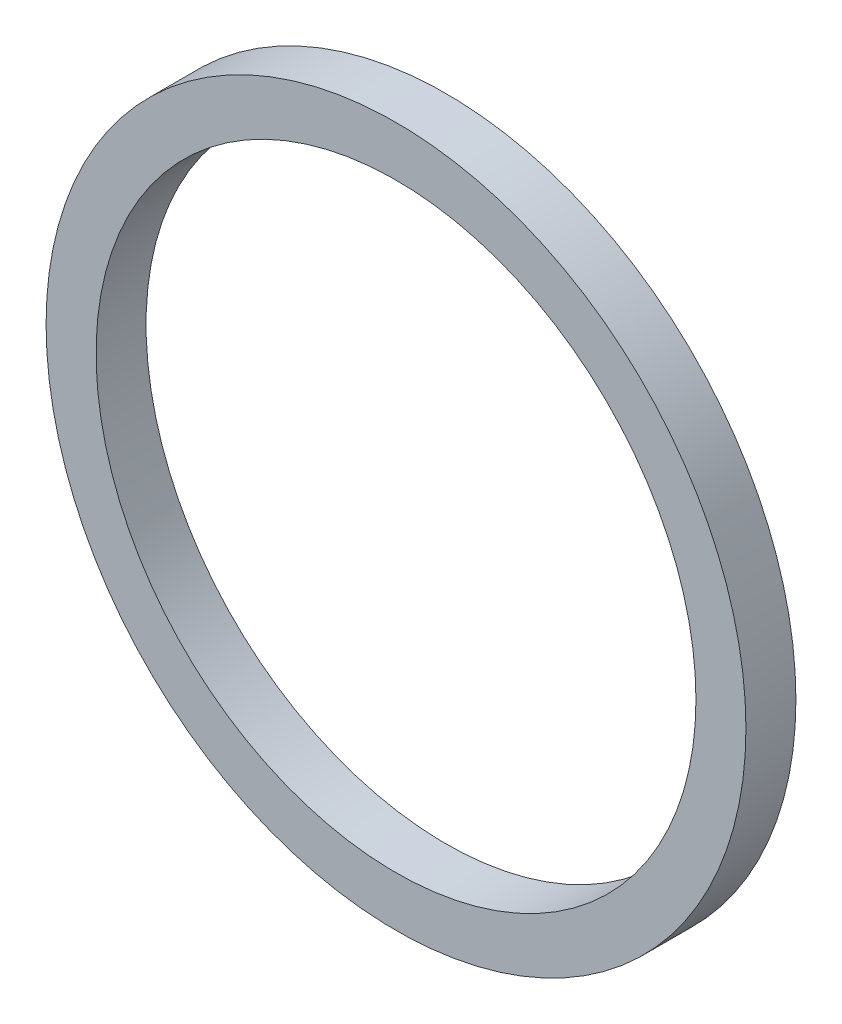
SolidWorks part; units mm, degrees
ref_plane "前视基准面" through (0, 0, 0) normal (0, 0, 1) x (1, 0, 0)
ref_plane "上视基准面" through (0, 0, 0) normal (0, 1, 0) x (1, 0, 0)
ref_plane "右视基准面" through (0, 0, 0) normal (1, 0, 0) x (0, 0, -1)
sketch "草图1" plane through (0, 0, 0) normal (0, 0, 1) x (1, 0, 0)
  circle A0 centre (0, 0) radius 6
  circle A1 centre (0, 0) radius 7
  dimension "D1" = 12
  dimension "D2" = 14
extrude "凸台-拉伸1" add sketch "草图1" along normal blind 1
